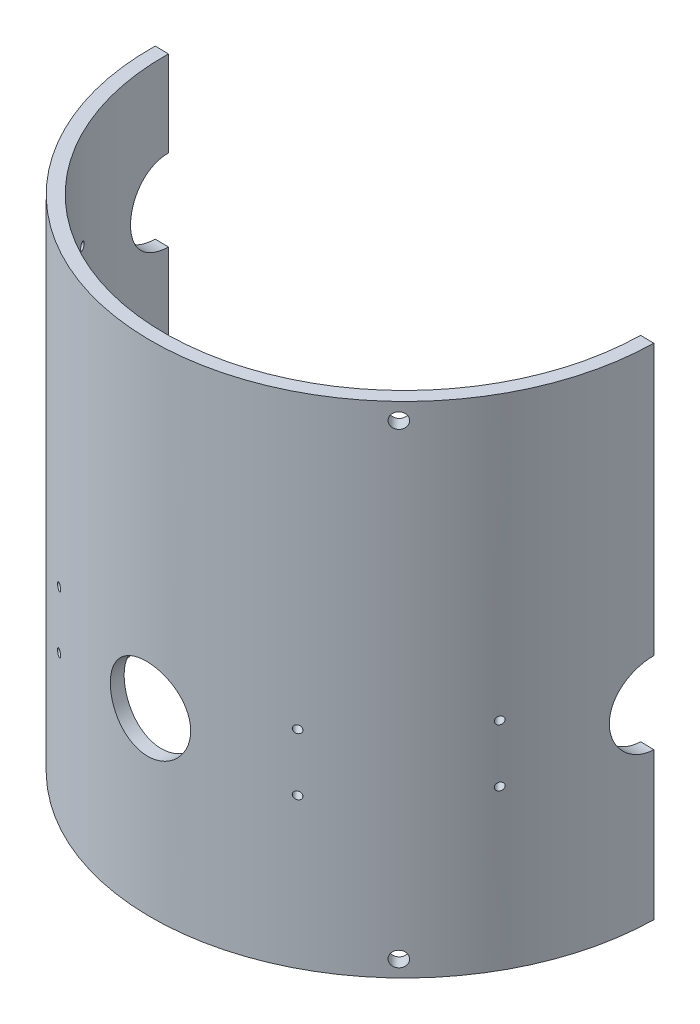
SolidWorks part; units mm, degrees
material "6061 Alloy"
ref_plane "Front Plane" through (0, 0, 0) normal (0, 0, 1) x (1, 0, 0)
ref_plane "Top Plane" through (0, 0, 0) normal (0, 1, 0) x (1, 0, 0)
ref_plane "Right Plane" through (0, 0, 0) normal (1, 0, 0) x (0, 0, -1)
sketch "Sketch1" plane through (0, 0, 0) normal (0, 1, 0) x (0.9999, 0, 0.016)
  line L0 (70.3723, 4.8181) -> (66.8563, 4.8181)
  line L1 (-62.3677, 4.8181) -> (-58.8517, 4.8181)
  arc A1 (-58.8517, 4.8181) -> (66.8563, 4.8181) centre (4.0023, 4.8181) ccw
  arc A3 (-62.3677, 4.8181) -> (70.3723, 4.8181) centre (4.0023, 4.8181) ccw
extrude "Boss-Extrude1" add sketch "Sketch1" along normal blind 130.8
extrude "Cut-Extrude4" cut sketch "Sketch5" along normal blind 129.8
sketch "Sketch5" plane through (63.6879, 47.8999, -8.6213) normal (0.9999, 0, 0.016) x (0.016, 0, -0.9999)
  line L0 (-4.8181, 26.3001) -> (-4.8181, -23.5999) construction
  circle A0 centre (-4.8181, 1.3501) radius 10.65
extrude "Cut-Extrude5" cut sketch "Sketch6" along normal blind 129.8
sketch "Sketch6" plane through (-55.377, 47.8999, -10.5208) normal (-0.9999, 0, -0.016) x (-0.016, 0, 0.9999)
  line L0 (4.8181, 73.2001) -> (4.8181, 26.3001) construction
  line L3 (4.8181, 26.3001) -> (17.3181, 26.3001) construction
  circle A0 centre (4.8181, 49.7501) radius 10.65
extrude "Cut-Extrude6" [suppressed] cut sketch "Sketch7" against normal blind 178 and the other way through all
sketch "Sketch7" plane through (3.6773, 47.8999, -5.168) normal (-0.7183, 0, 0.6957) x (0.6957, 0, 0.7183)
  circle A0 centre (0.5768, 78.0501) radius 2
sketch "Sketch8" plane through (0, 0, 0) normal (0, 0, 1) x (1, 0, 0)
  point P8 (68.4244, 64.9)
  point P9 (-60.2672, 64.9)
  point P12 (-9.4845, 64.9)
sketch "Sketch9" plane through (0, 0, 0) normal (1, 0, 0) x (0, 0, -1)
  point P4 (-59.6004, 64.9)
ref_plane "Plane1" through (0, 64.9, 0) normal (0, -1, 0) x (1, 0, 0)
extrude "Cut-Extrude7" [suppressed] cut sketch "Sketch10" along normal through all
sketch "Sketch10" plane through (8.5586, 47.8999, -9.0929) normal (0.6957, 0, 0.7183) x (0.7183, 0, -0.6957)
  circle A0 centre (-6.2369, 78.0501) radius 2
mirror "Mirror1" [suppressed] about plane through (0, 64.9, 0) normal (0, -1, 0)
sketch "Sketch11" plane through (0, 130.8, 0) normal (0, 1, 0) x (1, 0, 0)
  line L0 (-56.7516, 5.724) -> (64.9089, 3.7832)
  line L2 (4.0786, 4.7536) -> (3.0169, -61.7999)
sketch "Sketch13" plane through (0, 0, 0) normal (0, -1, 0) x (1, 0, 0)
  line L0 (-56.7516, -5.724) -> (64.9089, -3.7832)
  line L1 (4.0786, -4.7536) -> (3.0169, 61.7999)
ref_plane "Plane2" through (4.0018, 0, 0.0638) normal (0.9999, 0, 0.016) x (0.016, 0, -0.9999)
sketch "Sketch14" plane through (4.0018, 0, 0.0638) normal (0.9999, 0, 0.016) x (0.016, 0, -0.9999)
  line L0 (4.8181, 59.9) -> (4.8181, 64.9) construction
  line L2 (-5.8319, 49.25) -> (-10.8319, 49.25) construction
  line L3 (4.8181, 59.9) -> (4.8181, 64.9)
  line L4 (4.8181, 64.9) -> (-10.8319, 64.9)
  line L5 (-10.8319, 64.9) -> (-10.8319, 33.6)
  line L6 (4.8181, 38.6) -> (4.8181, 33.6)
  line L7 (4.8181, 33.6) -> (-10.8319, 33.6)
  arc A1 (4.8181, 59.9) -> (4.8181, 38.6) centre (4.8181, 49.25) ccw
  dimension "D1" = 5
  dimension "D2" = 5
sketch "Sketch15" plane through (4.0018, 0, 0.0638) normal (0.9999, 0, 0.016) x (0.016, 0, -0.9999)
  line L0 (4.8181, 108.3) -> (4.8181, 113.3) construction
  line L2 (-5.8319, 97.65) -> (-10.8319, 97.65) construction
  line L3 (4.8181, 108.3) -> (4.8181, 113.3)
  line L4 (4.8181, 113.3) -> (-10.8319, 113.3)
  line L5 (-10.8319, 113.3) -> (-10.8319, 82)
  line L6 (4.8181, 82) -> (-10.8319, 82)
  line L7 (4.8181, 87) -> (4.8181, 82)
  arc A1 (4.8181, 108.3) -> (4.8181, 87) centre (4.8181, 97.65) ccw
  dimension "D1" = 5
  dimension "D2" = 5
sketch "Sketch16" plane through (0, 130.8, 0) normal (0, 1, 0) x (1, 0, 0)
  circle A0 centre (4.0786, 4.7536) radius 60.838
extrude "Cut-Extrude48" cut sketch "Sketch57" against normal through all
sketch "Sketch57" plane through (-1.3359, 38.8999, 83.7413) normal (-0.016, 0, 0.9999) x (0.9999, 0, 0.016)
  circle A0 centre (4.0023, 7.9001) radius 10.7
extrude "Cut-Extrude51" cut sketch "Sketch60" along normal through all and the other way through all
sketch "Sketch60" plane through (4.4795, 38.8999, -4.3398) normal (-0.7182, 0, 0.6958) x (0.6958, 0, 0.7182)
  line L0 (-0.5762, 87.5501) -> (-0.5762, -34.5999) construction
  circle A0 centre (-0.5762, 87.5501) radius 2
  circle A1 centre (-0.5762, -34.5999) radius 2
extrude "Cut-Extrude52" cut sketch "Sketch61" against normal through all and the other way through all
sketch "Sketch61" plane through (-0.4009, 38.8999, -0.4138) normal (0.6958, 0, 0.7182) x (0.7182, 0, -0.6958)
  line L0 (6.237, -34.5999) -> (6.237, 87.5501) construction
  circle A0 centre (6.237, 87.5501) radius 2
  circle A1 centre (6.237, -34.5999) radius 2
extrude "Cut-Extrude53" cut sketch "Sketch63" against normal through all
sketch "Sketch63" plane through (48.515, 38.8999, 50.088) normal (0.6957, 0, 0.7183) x (0.7183, 0, -0.6957)
  circle A0 centre (-12.5511, 15.4001) radius 1
  circle A1 centre (-12.5511, 0.4001) radius 1
extrude "Cut-Extrude54" cut sketch "Sketch64" against normal through all
sketch "Sketch64" plane through (-46.0224, 38.8999, 44.577) normal (-0.7183, 0, 0.6957) x (0.6957, 0, 0.7183)
  circle A0 centre (18.0696, 15.4001) radius 1
  circle A1 centre (18.0696, 0.4001) radius 1
extrude "Cut-Extrude55" cut sketch "Sketch65" against normal through all
sketch "Sketch65" plane through (-46.0224, 38.8999, 44.577) normal (-0.7183, 0, 0.6957) x (0.6957, 0, 0.7183)
  circle A0 centre (-19.3649, 66.2501) radius 1
  circle A1 centre (-19.3649, 51.2501) radius 1
extrude "Cut-Extrude56" cut sketch "Sketch66" against normal through all
sketch "Sketch66" plane through (48.515, 38.8999, 50.088) normal (0.6957, 0, 0.7183) x (0.7183, 0, -0.6957)
  circle A0 centre (24.8833, 17.8501) radius 1
  circle A1 centre (24.8833, 2.8501) radius 1
sketch "Sketch68" plane through (0, 130.8, 0) normal (0, 1, 0) x (1, 0, 0)
  line L0 (-62.2829, 5.8123) -> (70.4402, 3.695)
sketch "Sketch69" plane through (0, 0, 0) normal (0, -1, 0) x (1, 0, 0)
  line L0 (-62.2829, -5.8123) -> (70.4402, -3.695)
ref_plane "Plane3" through (0.0769, 0, -4.8175) normal (-0.016, 0, 0.9999) x (0.9999, 0, 0.016)
